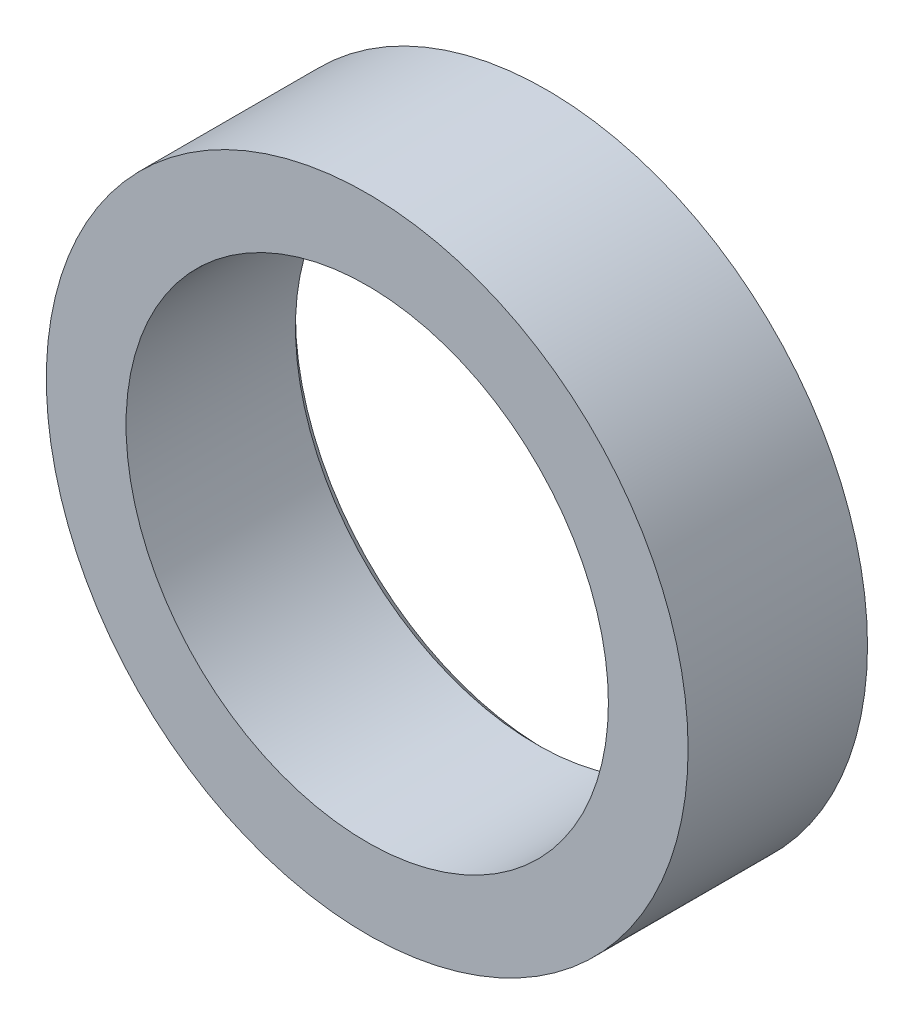
SolidWorks part; units mm, degrees
ref_plane "Piano frontale" through (0, 0, 0) normal (0, 0, 1) x (1, 0, 0)
ref_plane "Piano superiore" through (0, 0, 0) normal (0, 1, 0) x (1, 0, 0)
ref_plane "Piano destro" through (0, 0, 0) normal (1, 0, 0) x (0, 0, -1)
sketch "Schizzo1" plane through (0, 0, 0) normal (0, 0, 1) x (1, 0, 0)
  circle A0 centre (0, 0) radius 12.1
  circle A1 centre (0, 0) radius 16.1
  dimension "D1" = 4
  dimension "D2" = 24.2
extrude "Estrusione-Estrusione1" add sketch "Schizzo1" along normal blind 9
chamfer "Smusso1" distance 0.5 angle 45 1 edges at (12.1, 0, 0)
